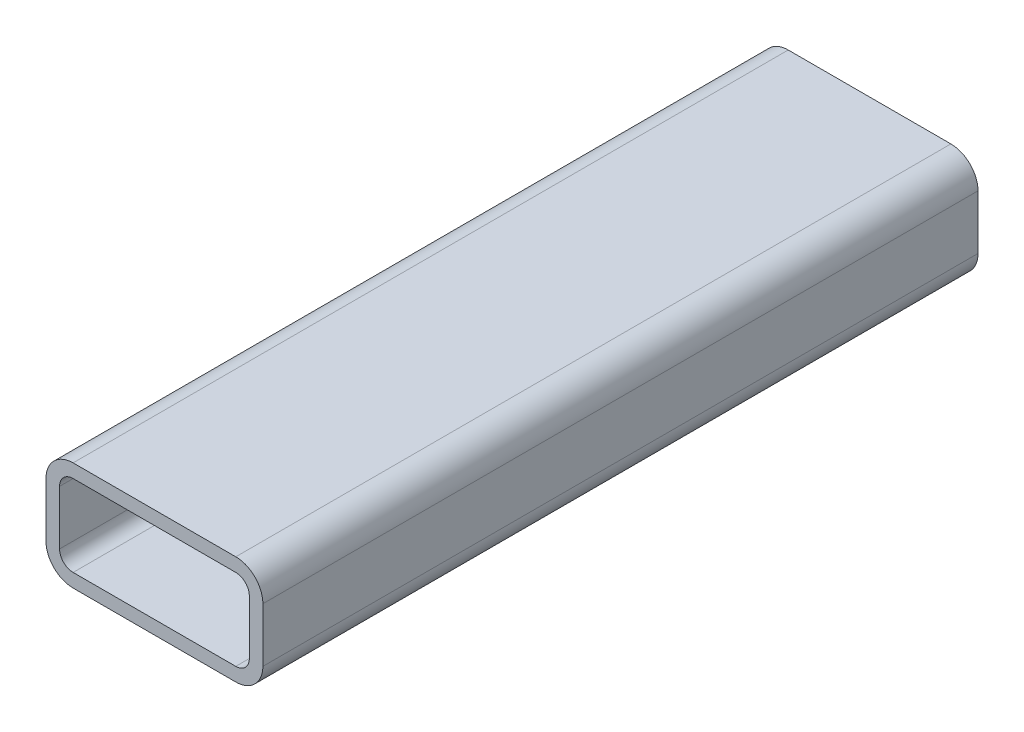
SolidWorks part; units mm, degrees
material "Low Carbon Steel"
ref_plane "Front Plane" through (0, 0, 0) normal (0, 0, 1) x (1, 0, 0)
ref_plane "Top Plane" through (0, 0, 0) normal (0, 1, 0) x (1, 0, 0)
ref_plane "Right Plane" through (0, 0, 0) normal (1, 0, 0) x (0, 0, -1)
sketch "Sketch1" plane through (0, 0, 0) normal (0, 0, 1) x (1, 0, 0)
  line L0 (-76.2, -38.1) -> (76.2, -38.1)
  line L1 (-88.9, -25.4) -> (-88.9, 25.4)
  line L2 (76.2, 38.1) -> (-76.2, 38.1)
  line L3 (88.9, 25.4) -> (88.9, -25.4)
  line L4 (-76.2, -50.8) -> (76.2, -50.8)
  line L5 (-101.6, -25.4) -> (-101.6, 25.4)
  line L6 (76.2, 50.8) -> (-76.2, 50.8)
  line L7 (101.6, 25.4) -> (101.6, -25.4)
  line L10 (0, 38.1) -> (0, -38.1) construction
  arc A0 (101.6, 25.4) -> (76.2, 50.8) centre (76.2, 25.4) ccw
  arc A1 (76.2, -50.8) -> (101.6, -25.4) centre (76.2, -25.4) ccw
  arc A2 (-101.6, -25.4) -> (-76.2, -50.8) centre (-76.2, -25.4) ccw
  arc A3 (-76.2, 50.8) -> (-101.6, 25.4) centre (-76.2, 25.4) ccw
  arc A4 (-76.2, 38.1) -> (-88.9, 25.4) centre (-76.2, 25.4) ccw
  arc A5 (88.9, 25.4) -> (76.2, 38.1) centre (76.2, 25.4) ccw
  arc A6 (76.2, -38.1) -> (88.9, -25.4) centre (76.2, -25.4) ccw
  arc A7 (-88.9, -25.4) -> (-76.2, -38.1) centre (-76.2, -25.4) ccw
extrude "Boss-Extrude1" add sketch "Sketch1" along normal blind 670
